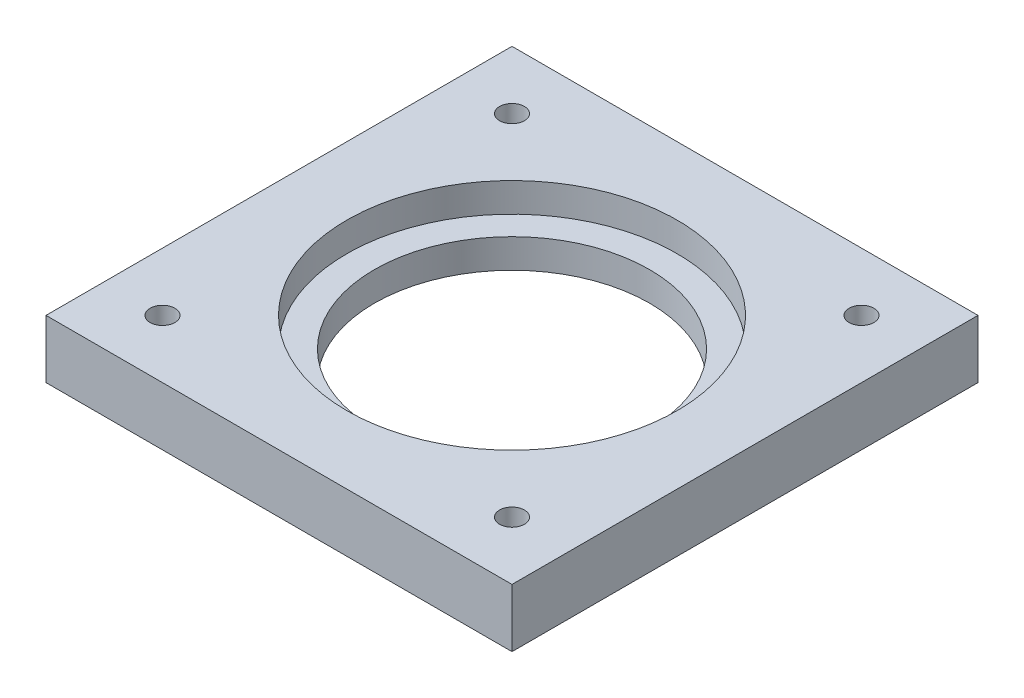
SolidWorks part; units mm, degrees
material "1060 Alloy"
ref_plane "Front Plane" through (0, 0, 0) normal (0, 0, 1) x (1, 0, 0)
ref_plane "Top Plane" through (0, 0, 0) normal (0, 1, 0) x (1, 0, 0)
ref_plane "Right Plane" through (0, 0, 0) normal (1, 0, 0) x (0, 0, -1)
sketch "Sketch2" plane through (0, 0, 0) normal (0, 1, 0) x (1, 0, 0)
  line L1 (0, 0) -> (-50.8, 0)
  line L2 (0, 0) -> (0, 50.8)
  line L3 (0, 50.8) -> (-50.8, 50.8)
  line L4 (-50.8, 0) -> (-50.8, 50.8)
  dimension "D1" = 50.8
  dimension "D2" = 50.8
extrude "Boss-Extrude1" add sketch "Sketch2" along normal blind 6.35
sketch "Sketch3" plane through (0, 6.35, 0) normal (0, 1, 0) x (1, 0, 0)
  line L0 (-50.8, 0) -> (0, 0) construction
  line L1 (0, 0) -> (0, 50.8) construction
  circle A0 centre (-25.4, 25.4) radius 18
  point P4 (-25.4, 0)
  point P7 (0, 25.4)
  dimension "D1" = 36
extrude "Cut-Extrude1" cut sketch "Sketch3" against normal blind 3.175
sketch "Sketch4" plane through (0, 0, 0) normal (0, -1, 0) x (-1, 0, 0)
  circle A0 centre (25.4, 25.4) radius 15
  dimension "D1" = 30
extrude "Cut-Extrude2" cut sketch "Sketch4" against normal through all
hole_wizard "Tap Drill for #6-32 Tap1" positions "Sketch6" profile "Sketch5" hole size "#6-32" standard "ANSI Inch" end condition through all
sketch "Sketch6" plane through (0, 0, 0) normal (0, -1, 0) x (-1, 0, 0)
  line L0 (0, 0) -> (0, 50.8) construction
  line L3 (50.8, 0) -> (0, 0) construction
  point P0 (6.35, 6.35)
  point P27 (6.35, 44.45)
  point P28 (44.45, 44.45)
  point P29 (44.45, 6.35)
  point P30 (25.4, 25.4)
  dimension "D1" = 6.35
  dimension "D2" = 6.35
  dimension "D3" = 4
sketch "Sketch5" plane through (-6.35, 0, -6.35) normal (1, 0, 0) x (0, 0, -1)
  line L0 (0, 0) -> (0, 6.35)
  line L1 (0, 6.35) -> (1.3525, 6.35)
  line L2 (1.3525, 6.35) -> (1.3525, 0)
  line L5 (1.3525, 0) -> (0, 0)
  line L11 (0, -6.35) -> (0, 107.95) construction
  dimension "Thru Hole Dia." = 2.7051
  dimension "Thru Hole Depth" = 6.35
